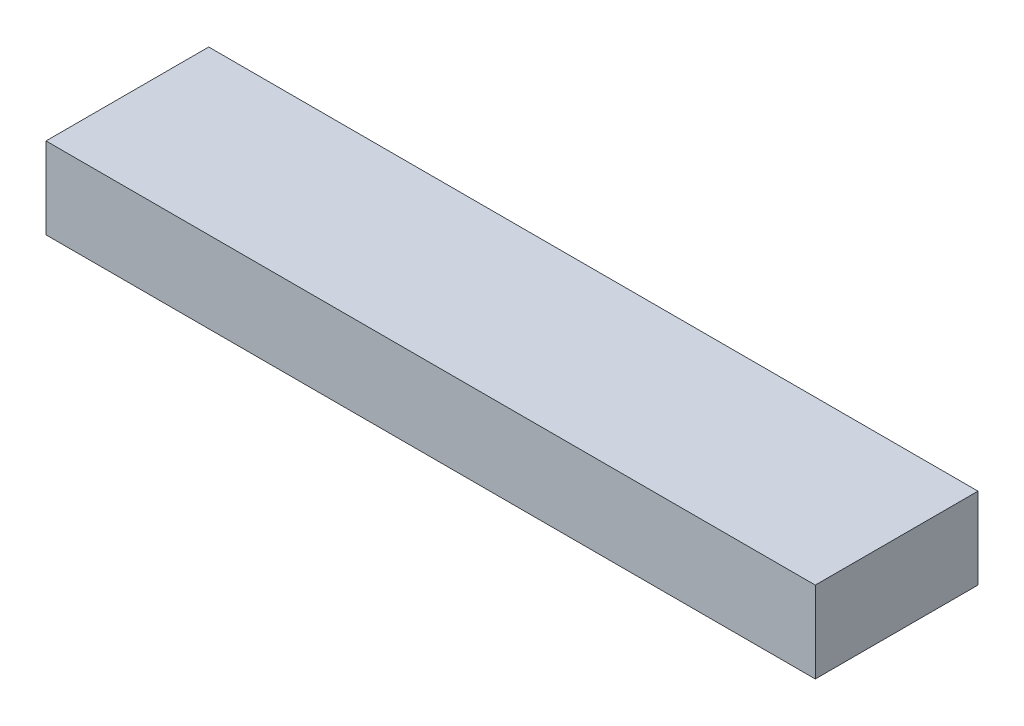
SolidWorks part; units mm, degrees
ref_plane "前视基准面" through (0, 0, 0) normal (0, 0, 1) x (1, 0, 0)
ref_plane "上视基准面" through (0, 0, 0) normal (0, 1, 0) x (1, 0, 0)
ref_plane "右视基准面" through (0, 0, 0) normal (1, 0, 0) x (0, 0, -1)
sketch "草图1" plane through (0, 0, 0) normal (0, 1, 0) x (1, 0, 0)
  line L0 (0, 0) -> (47.28, 0)
  line L1 (47.28, 0) -> (47.28, -10)
  line L2 (47.28, -10) -> (0, -10)
  line L3 (0, -10) -> (0, 0)
extrude "凸台-拉伸1" add sketch "草图1" along normal blind 5
